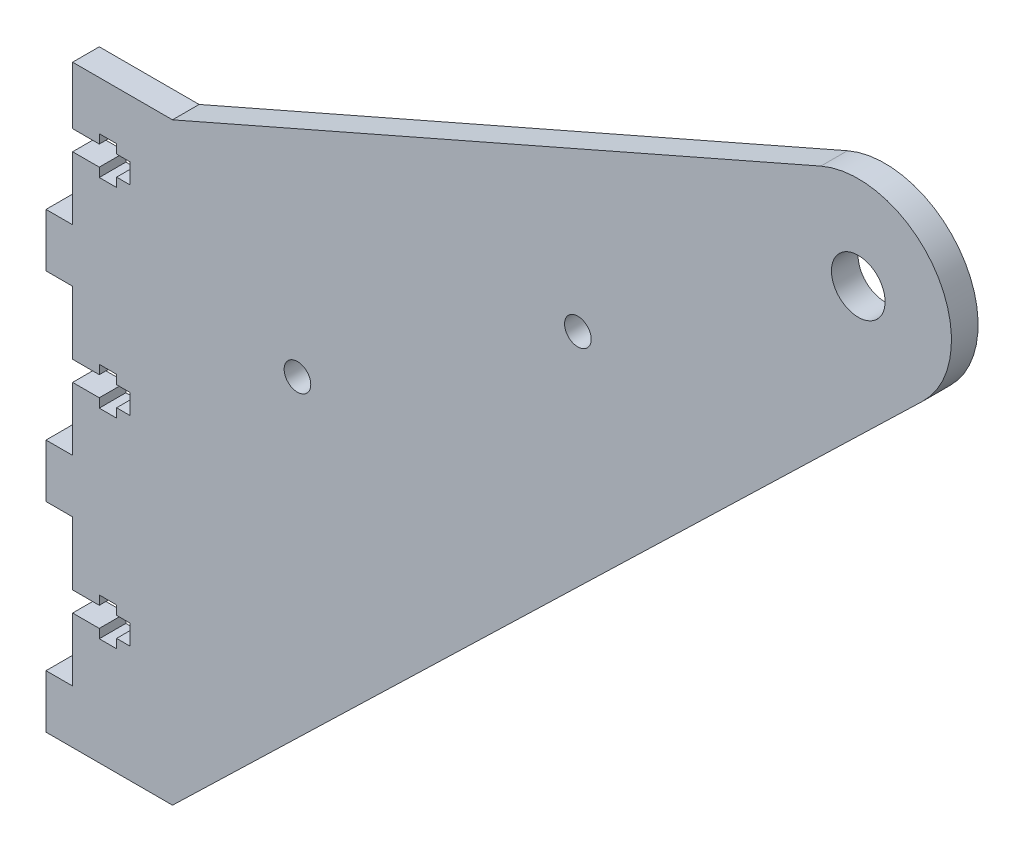
SolidWorks part; units mm, degrees
ref_plane "前视基准面" through (0, 0, 0) normal (0, 0, 1) x (1, 0, 0)
ref_plane "上视基准面" through (0, 0, 0) normal (0, 1, 0) x (1, 0, 0)
ref_plane "右视基准面" through (0, 0, 0) normal (1, 0, 0) x (0, 0, -1)
sketch "草图1" plane through (0, 0, 0) normal (0, 0, 1) x (1, 0, 0)
  line L0 (-1.7171, -22.1136) -> (2.2829, -22.1136)
  line L1 (2.2829, -22.1136) -> (2.2829, -23.4636)
  line L2 (2.2829, -23.4636) -> (4.8829, -23.4636)
  line L3 (4.8829, -23.4636) -> (4.8829, -22.1136)
  line L4 (4.8829, -22.1136) -> (6.8829, -22.1136)
  line L5 (6.8829, -22.1136) -> (6.8829, -19.1136)
  line L6 (-1.7171, -20.6136) -> (-3.0249, -20.6136) construction
  line L7 (-1.7171, -22.1136) -> (-1.7171, -19.1136) construction
  line L8 (4.8829, -17.7636) -> (4.8829, -19.1136)
  line L9 (2.2829, -19.1136) -> (2.2829, -17.7636)
  line L10 (4.8829, -19.1136) -> (6.8829, -19.1136)
  line L11 (2.2829, -17.7636) -> (4.8829, -17.7636)
  line L12 (-1.7171, -19.1136) -> (2.2829, -19.1136)
  line L13 (-1.7171, -39.6136) -> (-5.7171, -39.6136)
  line L14 (-5.7171, -39.6136) -> (-5.7171, -31.6136)
  line L15 (-5.7171, -31.6136) -> (-1.7171, -31.6136)
  line L16 (-1.7171, -31.6136) -> (-1.7171, -22.1136)
  line L17 (-5.7171, -35.6136) -> (-4.0142, -35.6136) construction
  line L18 (6.8829, 39.3864) -> (3.9614, 39.3864) construction
  line L19 (-5.7171, 24.3864) -> (-4.0142, 24.3864) construction
  line L20 (6.8829, 9.3864) -> (3.9614, 9.3864) construction
  line L21 (-5.7171, -5.6136) -> (-4.0142, -5.6136) construction
  line L22 (-1.7171, -22.1136) -> (2.2829, -22.1136)
  line L23 (2.2829, -22.1136) -> (2.2829, -23.4636)
  line L24 (2.2829, -23.4636) -> (4.8829, -23.4636)
  line L25 (4.8829, -23.4636) -> (4.8829, -22.1136)
  line L26 (4.8829, -22.1136) -> (6.8829, -22.1136)
  line L27 (4.8829, -17.7636) -> (4.8829, -19.1136)
  line L28 (2.2829, -19.1136) -> (2.2829, -17.7636)
  line L29 (4.8829, -19.1136) -> (6.8829, -19.1136)
  line L30 (-1.7171, -22.1136) -> (2.2829, -22.1136)
  line L31 (2.2829, -23.4636) -> (4.8829, -23.4636)
  line L32 (4.8829, -22.1136) -> (6.8829, -22.1136)
  line L33 (2.2829, -22.1136) -> (2.2829, -23.4636)
  line L34 (4.8829, -23.4636) -> (4.8829, -22.1136)
  line L35 (4.8829, -19.1136) -> (6.8829, -19.1136)
  line L36 (4.8829, -17.7636) -> (4.8829, -19.1136)
  line L37 (2.2829, -17.7636) -> (4.8829, -17.7636)
  line L38 (2.2829, -19.1136) -> (2.2829, -17.7636)
  line L39 (-1.7171, -19.1136) -> (2.2829, -19.1136)
  line L40 (2.2829, -17.7636) -> (4.8829, -17.7636)
  line L41 (-1.7171, -19.1136) -> (2.2829, -19.1136)
  line L42 (2.2829, 36.5364) -> (4.8829, 36.5364)
  line L43 (4.8829, 37.8864) -> (6.8829, 37.8864)
  line L44 (2.2829, 37.8864) -> (2.2829, 36.5364)
  line L45 (4.8829, 36.5364) -> (4.8829, 37.8864)
  line L46 (6.8829, 40.8864) -> (6.8829, 37.8864)
  line L47 (4.8829, 40.8864) -> (6.8829, 40.8864)
  line L48 (4.8829, 42.2364) -> (4.8829, 40.8864)
  line L49 (2.2829, 42.2364) -> (4.8829, 42.2364)
  line L50 (2.2829, 40.8864) -> (2.2829, 42.2364)
  line L51 (2.2829, 40.8864) -> (-1.7171, 40.8864)
  line L52 (2.2829, 37.8864) -> (-1.7171, 37.8864)
  line L53 (-1.7171, 28.3864) -> (-1.7171, 37.8864)
  line L54 (-1.7171, 20.3864) -> (-5.7171, 20.3864)
  line L55 (-5.7171, 20.3864) -> (-5.7171, 28.3864)
  line L56 (-5.7171, 28.3864) -> (-1.7171, 28.3864)
  line L57 (-1.7171, 7.8864) -> (-1.7171, -1.6136)
  line L58 (2.2829, 7.8864) -> (-1.7171, 7.8864)
  line L59 (2.2829, 10.8864) -> (-1.7171, 10.8864)
  line L60 (-1.7171, 20.3864) -> (-1.7171, 10.8864)
  line L61 (2.2829, 7.8864) -> (2.2829, 6.5364)
  line L62 (2.2829, 6.5364) -> (4.8829, 6.5364)
  line L63 (4.8829, 6.5364) -> (4.8829, 7.8864)
  line L64 (4.8829, 7.8864) -> (6.8829, 7.8864)
  line L65 (6.8829, 7.8864) -> (6.8829, 10.8864)
  line L66 (4.8829, 12.2364) -> (4.8829, 10.8864)
  line L67 (2.2829, 10.8864) -> (2.2829, 12.2364)
  line L68 (4.8829, 10.8864) -> (6.8829, 10.8864)
  line L69 (2.2829, 12.2364) -> (4.8829, 12.2364)
  line L70 (-1.7171, -9.6136) -> (-1.7171, -19.1136)
  line L71 (-5.7171, -9.6136) -> (-1.7171, -9.6136)
  line L72 (-5.7171, -1.6136) -> (-5.7171, -9.6136)
  line L73 (-1.7171, -1.6136) -> (-5.7171, -1.6136)
  line L74 (-1.7171, -22.1136) -> (2.2829, -22.1136)
  line L75 (2.2829, -23.4636) -> (4.8829, -23.4636)
  line L76 (4.8829, -22.1136) -> (6.8829, -22.1136)
  line L77 (2.2829, -22.1136) -> (2.2829, -23.4636)
  line L78 (4.8829, -23.4636) -> (4.8829, -22.1136)
  line L79 (4.8829, -19.1136) -> (6.8829, -19.1136)
  line L80 (4.8829, -17.7636) -> (4.8829, -19.1136)
  line L81 (2.2829, -17.7636) -> (4.8829, -17.7636)
  line L82 (2.2829, -19.1136) -> (2.2829, -17.7636)
  line L83 (-1.7171, -19.1136) -> (2.2829, -19.1136)
  line L84 (-1.7171, 40.8864) -> (-1.7171, 49.5381)
  line L85 (6.8829, -22.1136) -> (13.2829, -22.1136) construction
  line L86 (13.2829, -39.6136) -> (13.2829, 49.5381) construction
  line L88 (116.2829, 79.3864) -> (6.8829, 9.3864) construction
  line L89 (13.2829, -39.6136) -> (-1.7171, -39.6136)
  line L91 (116.2829, 28.2764) -> (116.2829, 79.3864) construction
  line L92 (13.2829, 49.5381) -> (110.664, 92.2094)
  line L93 (13.2829, -39.6136) -> (126.0114, 69.3189)
  line L94 (13.2829, 49.5381) -> (-1.7171, 49.5381)
  circle A3 centre (116.2829, 79.3864) radius 4.03
  arc A6 (126.0114, 69.3189) -> (110.664, 92.2094) centre (116.2829, 79.3864) ccw
  circle A7 centre (116.2829, 79.3864) radius 14 construction
  circle A9 centre (74.1665, 52.4381) radius 2
  circle A10 centre (32.0501, 25.4898) radius 2
  point P11 (-2.371, -20.6136)
  dimension "D8" = 8.06
  dimension "D9" = 118
  dimension "D14" = 50
  dimension "D1" = 4
  dimension "D2" = 2
  dimension "D3" = 2.6
  dimension "D4" = 1.35
  dimension "D5" = 1.5
  dimension "D6" = 9.5
  dimension "D7" = 15
  dimension "D11" = 40
  dimension "D15" = 50
extrude "凸台-拉伸1" add sketch "草图1" along normal blind 4
sketch "草图2" plane through (-1.7171, 0, 0) normal (-1, 0, 0) x (0, 0, 1)
  line L0 (2, -19.1136) -> (2, -22.1136)
  line L1 (4, -19.1136) -> (0, -19.1136) construction
  line L2 (4, -22.1136) -> (0, -22.1136) construction
  circle A0 centre (2, -20.6136) radius 1.5
